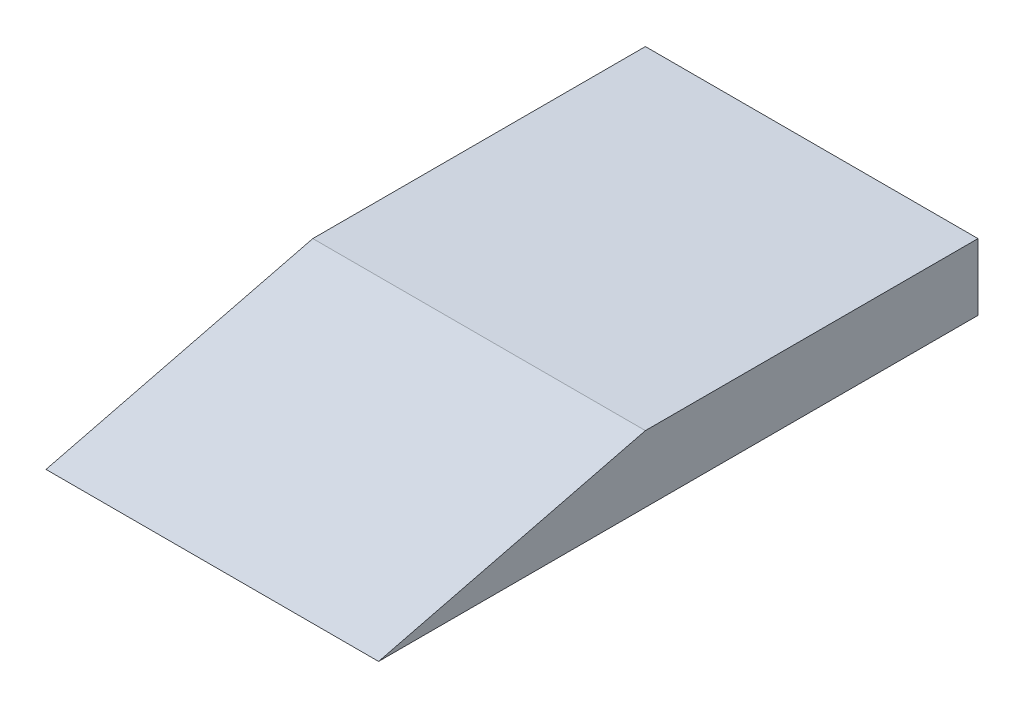
SolidWorks part; units mm, degrees
ref_plane "前视基准面" through (0, 0, 0) normal (0, 0, 1) x (1, 0, 0)
ref_plane "上视基准面" through (0, 0, 0) normal (0, 1, 0) x (1, 0, 0)
ref_plane "右视基准面" through (0, 0, 0) normal (1, 0, 0) x (0, 0, -1)
sketch "草图1" plane through (0, 0, 0) normal (1, 0, 0) x (0, 0, -1)
  line L0 (0, 200) -> (-802.1562, 0)
  line L1 (-802.1562, 0) -> (1000, 0)
  line L2 (0, 0) -> (0, 200) construction
  line L3 (0, 200) -> (1000, 200)
  line L4 (1000, 0) -> (1000, 200)
  dimension "D1" = 1000
  dimension "D2" = 200
  dimension "D3" = 76
extrude "凸台-拉伸1" add sketch "草图1" along normal blind 1000
